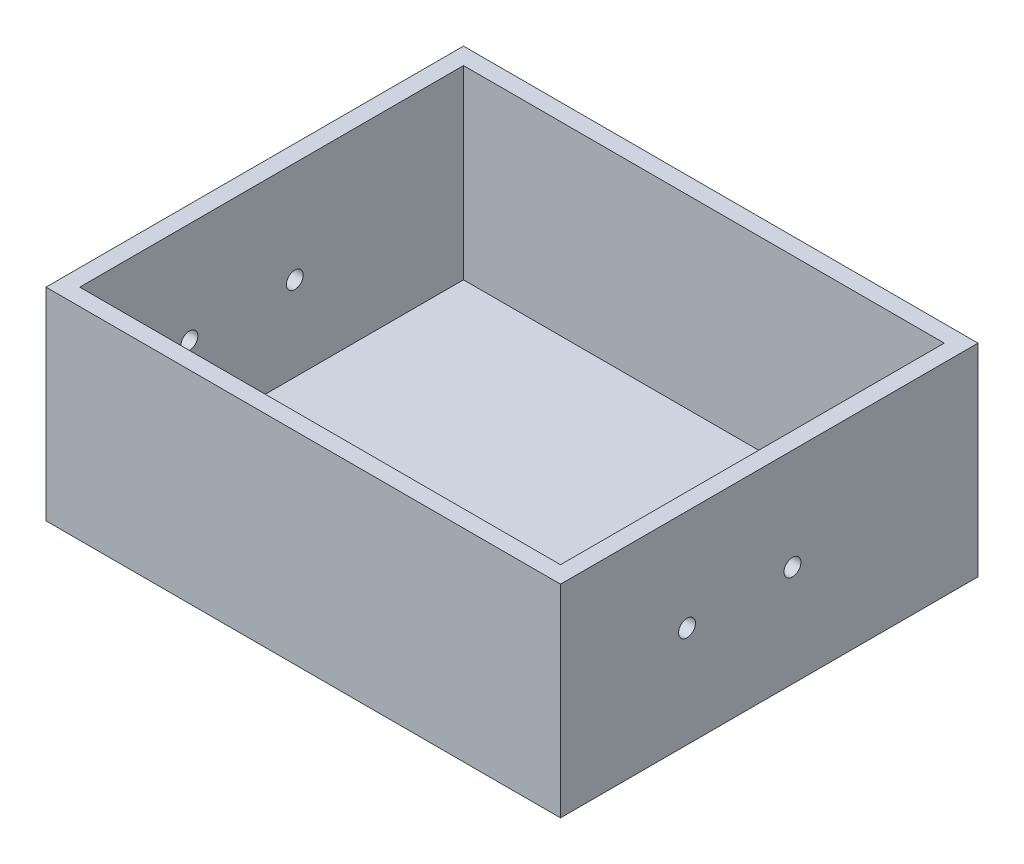
SolidWorks part; units mm, degrees
ref_plane "Front Plane" through (0, 0, 0) normal (0, 0, 1) x (1, 0, 0)
ref_plane "Top Plane" through (0, 0, 0) normal (0, 1, 0) x (1, 0, 0)
ref_plane "Right Plane" through (0, 0, 0) normal (1, 0, 0) x (0, 0, -1)
sketch "Sketch1" plane through (0, 0, 0) normal (0, 1, 0) x (1, 0, 0)
  line L1 (61, -49.5) -> (-61, -49.5)
  line L2 (61, -49.5) -> (61, 49.5)
  line L3 (61, 49.5) -> (-61, 49.5)
  line L4 (-61, -49.5) -> (-61, 49.5)
  point P0 (0, 0)
  point P6 (0, 0)
  dimension "D1" = 122
  dimension "D2" = 99
extrude "Boss-Extrude1" add sketch "Sketch1" along normal blind 48
sketch "Sketch2" plane through (0, 48, 0) normal (0, 1, 0) x (1, 0, 0)
  line L0 (61, -49.5) -> (61, 49.5) construction
  line L1 (-57, 45.5) -> (57, 45.5)
  line L2 (-57, 45.5) -> (-57, -45.5)
  line L3 (-57, -45.5) -> (57, -45.5)
  line L4 (57, 45.5) -> (57, -45.5)
  line L5 (-57, 45.5) -> (57, -45.5) construction
  line L6 (-57, -45.5) -> (57, 45.5) construction
  line L7 (-61, -49.5) -> (61, -49.5) construction
  point P0 (0, 0)
  dimension "D1" = 4
  dimension "D2" = 4
extrude "Cut-Extrude1" cut sketch "Sketch2" against normal blind 44
ref_plane "Plane1" through (61, 0, 0) normal (1, 0, 0) x (0, 0, -1)
sketch "Sketch3" plane through (61, 0, 0) normal (1, 0, 0) x (0, 0, -1)
  line L0 (-49.5, 24) -> (51.349, 24) construction
  line L1 (-49.5, 48) -> (-49.5, 0) construction
  circle A0 centre (-19.5, 24) radius 2
  circle A1 centre (5.5, 24) radius 2
  dimension "D1" = 4
  dimension "D2" = 4
  dimension "D3" = 25
  dimension "D4" = 30
extrude "Cut-Extrude2" cut sketch "Sketch3" against normal through all
